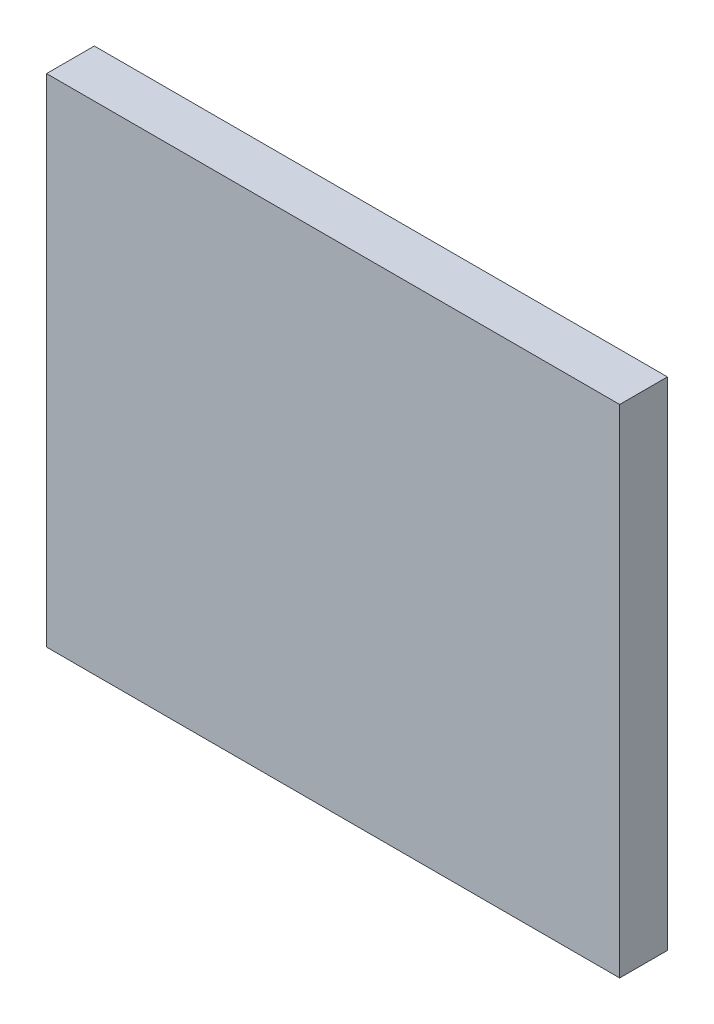
SolidWorks part; units mm, degrees
ref_plane "정면" through (0, 0, 0) normal (0, 0, 1) x (1, 0, 0)
ref_plane "윗면" through (0, 0, 0) normal (0, 1, 0) x (1, 0, 0)
ref_plane "우측면" through (0, 0, 0) normal (1, 0, 0) x (0, 0, -1)
sketch "스케치1" plane through (0, 0, 0) normal (0, 0, 1) x (1, 0, 0)
  line L1 (-30, 26) -> (30, 26)
  line L2 (-30, 26) -> (-30, -26)
  line L3 (-30, -26) -> (30, -26)
  line L4 (30, 26) -> (30, -26)
  line L5 (-30, 26) -> (30, -26) construction
  line L6 (-30, -26) -> (30, 26) construction
  point P0 (0, 0)
  dimension "D1" = 52
  dimension "D2" = 60
extrude "보스-돌출1" add sketch "스케치1" along normal blind 5
